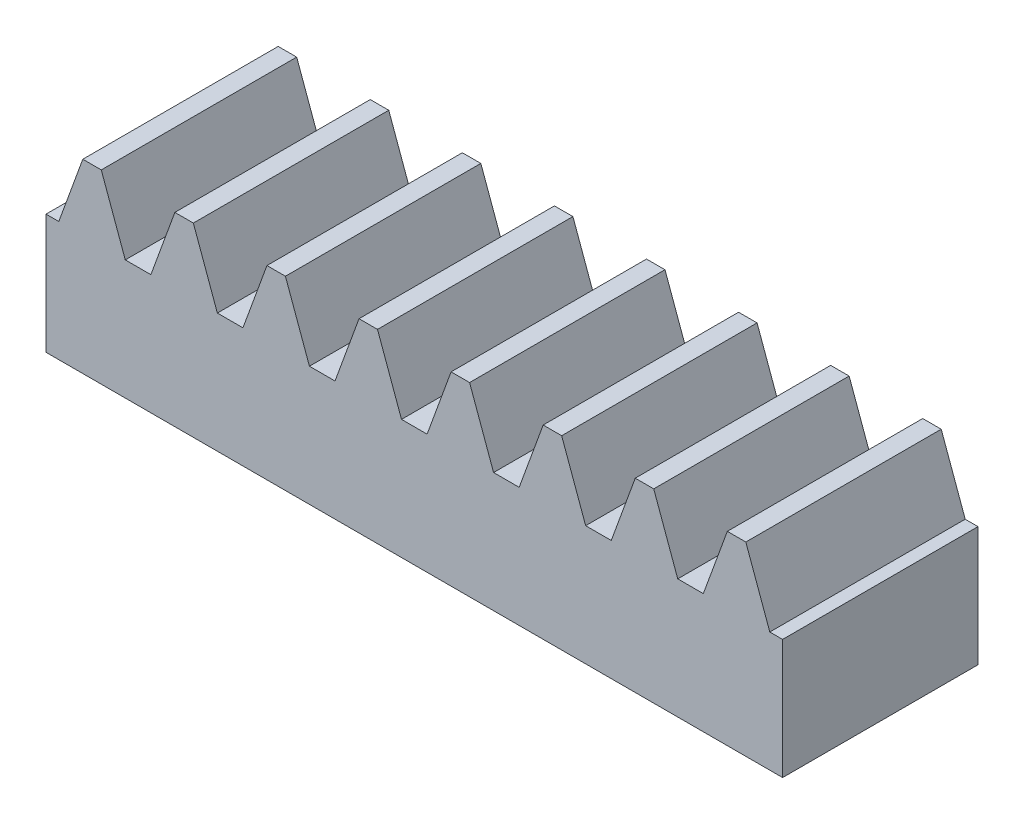
SolidWorks part; units mm, degrees
ref_plane "Plane1" through (0, 0, 0) normal (0, 0, 1) x (1, 0, 0)
ref_plane "Plane2" through (0, 0, 0) normal (0, 1, 0) x (1, 0, 0)
ref_plane "Plane3" through (0, 0, 0) normal (1, 0, 0) x (0, 0, -1)
sketch "Croquis3" plane through (0, 0, 0) normal (0, 0, 1) x (1, 0, 0)
  line B0 (32.3321, 6.125) -> (31.1037, 9.5)
  line B1 (33.6414, 6.125) -> (32.3321, 6.125)
  line B2 (34.8698, 9.5) -> (33.6414, 6.125)
  line B3 (35.8161, 9.5) -> (34.8698, 9.5)
  line B4 (37.0445, 6.125) -> (35.8161, 9.5)
  line B5 (37.6991, 6.125) -> (37.0445, 6.125)
  line B6 (0, 0) -> (37.6991, 0)
  line B7 (22.9073, 6.125) -> (21.6789, 9.5)
  line B8 (24.2166, 6.125) -> (22.9073, 6.125)
  line B9 (25.445, 9.5) -> (24.2166, 6.125)
  line B10 (26.3913, 9.5) -> (25.445, 9.5)
  line B11 (27.6197, 6.125) -> (26.3913, 9.5)
  line B12 (28.929, 6.125) -> (27.6197, 6.125)
  line B13 (30.1574, 9.5) -> (28.929, 6.125)
  line B14 (31.1037, 9.5) -> (30.1574, 9.5)
  line B15 (13.4825, 6.125) -> (12.2541, 9.5)
  line B16 (14.7918, 6.125) -> (13.4825, 6.125)
  line B17 (16.0202, 9.5) -> (14.7918, 6.125)
  line B18 (16.9665, 9.5) -> (16.0202, 9.5)
  line B19 (18.1949, 6.125) -> (16.9665, 9.5)
  line B20 (19.5042, 6.125) -> (18.1949, 6.125)
  line B21 (20.7326, 9.5) -> (19.5042, 6.125)
  line B22 (21.6789, 9.5) -> (20.7326, 9.5)
  line B23 (4.0577, 6.125) -> (2.8293, 9.5)
  line B24 (5.367, 6.125) -> (4.0577, 6.125)
  line B25 (6.5954, 9.5) -> (5.367, 6.125)
  line B26 (7.5417, 9.5) -> (6.5954, 9.5)
  line B27 (8.7701, 6.125) -> (7.5417, 9.5)
  line B28 (10.0794, 6.125) -> (8.7701, 6.125)
  line B29 (11.3078, 9.5) -> (10.0794, 6.125)
  line B30 (12.2541, 9.5) -> (11.3078, 9.5)
  line B31 (37.6991, 6.125) -> (37.6991, 0)
  line B32 (0, 6.125) -> (0, 0)
  line B33 (0.6547, 6.125) -> (0, 6.125)
  line B34 (1.8831, 9.5) -> (0.6547, 6.125)
  line B35 (2.8293, 9.5) -> (1.8831, 9.5)
sketch_block_instance "Bloque1-1"
sketch_block "Bloque1"
sketch "Croquis4" plane through (0, 0, 0) normal (0, 0, 1) x (1, 0, 0)
  line L0 (32.3321, 6.125) -> (31.1037, 9.5) construction
  line L1 (33.6414, 6.125) -> (32.3321, 6.125) construction
  line L2 (34.8698, 9.5) -> (33.6414, 6.125) construction
  line L3 (35.8161, 9.5) -> (34.8698, 9.5) construction
  line L4 (37.0445, 6.125) -> (35.8161, 9.5) construction
  line L5 (37.6991, 6.125) -> (37.0445, 6.125) construction
  line L6 (0, 0) -> (37.6991, 0) construction
  line L7 (22.9073, 6.125) -> (21.6789, 9.5) construction
  line L8 (24.2166, 6.125) -> (22.9073, 6.125) construction
  line L9 (25.445, 9.5) -> (24.2166, 6.125) construction
  line L10 (26.3913, 9.5) -> (25.445, 9.5) construction
  line L11 (27.6197, 6.125) -> (26.3913, 9.5) construction
  line L12 (28.929, 6.125) -> (27.6197, 6.125) construction
  line L13 (30.1574, 9.5) -> (28.929, 6.125) construction
  line L14 (31.1037, 9.5) -> (30.1574, 9.5) construction
  line L15 (13.4825, 6.125) -> (12.2541, 9.5) construction
  line L16 (14.7918, 6.125) -> (13.4825, 6.125) construction
  line L17 (16.0202, 9.5) -> (14.7918, 6.125) construction
  line L18 (16.9665, 9.5) -> (16.0202, 9.5) construction
  line L19 (18.1949, 6.125) -> (16.9665, 9.5) construction
  line L20 (19.5042, 6.125) -> (18.1949, 6.125) construction
  line L21 (20.7326, 9.5) -> (19.5042, 6.125) construction
  line L22 (21.6789, 9.5) -> (20.7326, 9.5) construction
  line L23 (4.0577, 6.125) -> (2.8293, 9.5) construction
  line L24 (5.367, 6.125) -> (4.0577, 6.125) construction
  line L25 (6.5954, 9.5) -> (5.367, 6.125) construction
  line L26 (7.5417, 9.5) -> (6.5954, 9.5) construction
  line L27 (8.7701, 6.125) -> (7.5417, 9.5) construction
  line L28 (10.0794, 6.125) -> (8.7701, 6.125) construction
  line L29 (11.3078, 9.5) -> (10.0794, 6.125) construction
  line L30 (12.2541, 9.5) -> (11.3078, 9.5) construction
  line L31 (37.6991, 6.125) -> (37.6991, 0) construction
  line L32 (0, 6.125) -> (0, 0) construction
  line L33 (0.6547, 6.125) -> (0, 6.125) construction
  line L34 (1.8831, 9.5) -> (0.6547, 6.125) construction
  line L35 (2.8293, 9.5) -> (1.8831, 9.5) construction
  line L36 (32.3321, 6.125) -> (31.1037, 9.5)
  line L37 (33.6414, 6.125) -> (32.3321, 6.125)
  line L38 (34.8698, 9.5) -> (33.6414, 6.125)
  line L39 (35.8161, 9.5) -> (34.8698, 9.5)
  line L40 (37.0445, 6.125) -> (35.8161, 9.5)
  line L41 (37.6991, 6.125) -> (37.0445, 6.125)
  line L42 (0, 0) -> (37.6991, 0)
  line L43 (22.9073, 6.125) -> (21.6789, 9.5)
  line L44 (24.2166, 6.125) -> (22.9073, 6.125)
  line L45 (25.445, 9.5) -> (24.2166, 6.125)
  line L46 (26.3913, 9.5) -> (25.445, 9.5)
  line L47 (27.6197, 6.125) -> (26.3913, 9.5)
  line L48 (28.929, 6.125) -> (27.6197, 6.125)
  line L49 (30.1574, 9.5) -> (28.929, 6.125)
  line L50 (31.1037, 9.5) -> (30.1574, 9.5)
  line L51 (13.4825, 6.125) -> (12.2541, 9.5)
  line L52 (14.7918, 6.125) -> (13.4825, 6.125)
  line L53 (16.0202, 9.5) -> (14.7918, 6.125)
  line L54 (16.9665, 9.5) -> (16.0202, 9.5)
  line L55 (18.1949, 6.125) -> (16.9665, 9.5)
  line L56 (19.5042, 6.125) -> (18.1949, 6.125)
  line L57 (20.7326, 9.5) -> (19.5042, 6.125)
  line L58 (21.6789, 9.5) -> (20.7326, 9.5)
  line L59 (4.0577, 6.125) -> (2.8293, 9.5)
  line L60 (5.367, 6.125) -> (4.0577, 6.125)
  line L61 (6.5954, 9.5) -> (5.367, 6.125)
  line L62 (7.5417, 9.5) -> (6.5954, 9.5)
  line L63 (8.7701, 6.125) -> (7.5417, 9.5)
  line L64 (10.0794, 6.125) -> (8.7701, 6.125)
  line L65 (11.3078, 9.5) -> (10.0794, 6.125)
  line L66 (12.2541, 9.5) -> (11.3078, 9.5)
  line L67 (37.6991, 6.125) -> (37.6991, 0)
  line L68 (0, 6.125) -> (0, 0)
  line L69 (0.6547, 6.125) -> (0, 6.125)
  line L70 (1.8831, 9.5) -> (0.6547, 6.125)
  line L71 (2.8293, 9.5) -> (1.8831, 9.5)
extrude "Extruir1" add sketch "Croquis4" along normal blind 10
